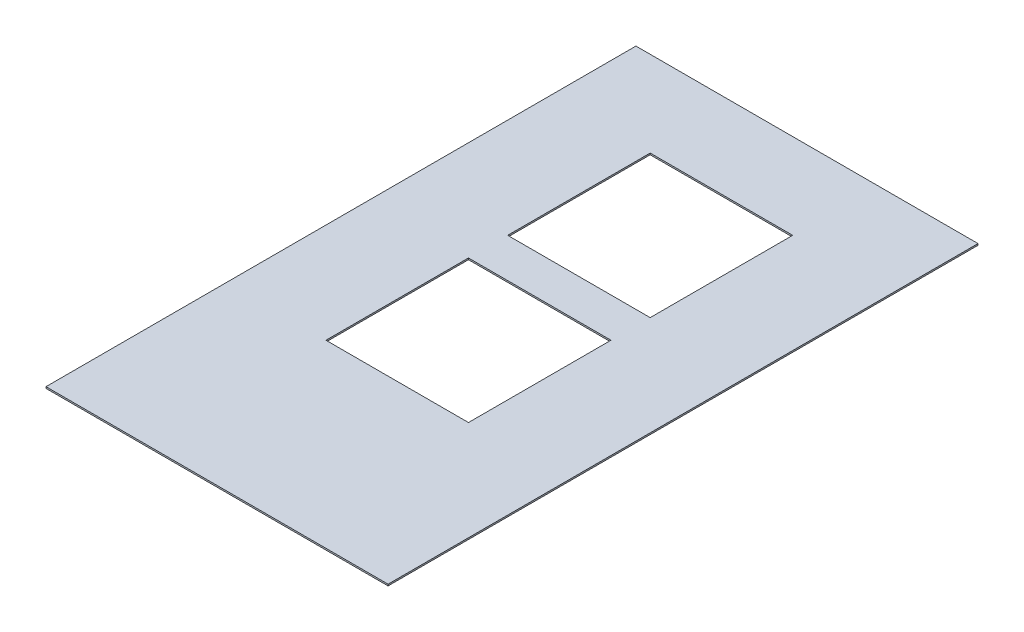
SolidWorks part; units mm, degrees
material "Teak"
ref_plane "Front Plane" through (0, 0, 0) normal (0, 0, 1) x (1, 0, 0)
ref_plane "Top Plane" through (0, 0, 0) normal (0, 1, 0) x (1, 0, 0)
ref_plane "Right Plane" through (0, 0, 0) normal (1, 0, 0) x (0, 0, -1)
sketch "Sketch1" plane through (0, 0, 0) normal (0, 1, 0) x (1, 0, 0)
  line L1 (-609.6, -1051.3219) -> (609.6, -1051.3219)
  line L2 (-609.6, -1051.3219) -> (-609.6, 1051.3219)
  line L3 (-609.6, 1051.3219) -> (609.6, 1051.3219)
  line L4 (609.6, -1051.3219) -> (609.6, 1051.3219)
  line L5 (-609.6, -1051.3219) -> (609.6, 1051.3219) construction
  line L6 (-609.6, 1051.3219) -> (609.6, -1051.3219) construction
  point P0 (0, 0)
  dimension "D1" = 1219.2
  dimension "D2" = 2102.6437
extrude "Boss-Extrude1" add sketch "Sketch1" along normal blind 5.5562
sketch "Sketch2" plane through (0, 0, 0) normal (0, -1, 0) x (-1, 0, 0)
  line L1 (-254, 238.5219) -> (254, 238.5219)
  line L2 (-254, 238.5219) -> (-254, 746.5219)
  line L3 (-254, 746.5219) -> (254, 746.5219)
  line L4 (254, 238.5219) -> (254, 746.5219)
  line L5 (-254, 238.5219) -> (254, 746.5219) construction
  line L6 (-254, 746.5219) -> (254, 238.5219) construction
  line L7 (-254, -409.1781) -> (254, -409.1781)
  line L8 (-254, -409.1781) -> (-254, 98.8219)
  line L9 (-254, 98.8219) -> (254, 98.8219)
  line L10 (254, -409.1781) -> (254, 98.8219)
  line L11 (-254, -409.1781) -> (254, 98.8219) construction
  line L12 (-254, 98.8219) -> (254, -409.1781) construction
  point P0 (0, 492.5219)
  point P6 (0, -155.1781)
  dimension "D1" = 508
extrude "Cut-Extrude1" cut sketch "Sketch2" against normal through all both and the other way through all
